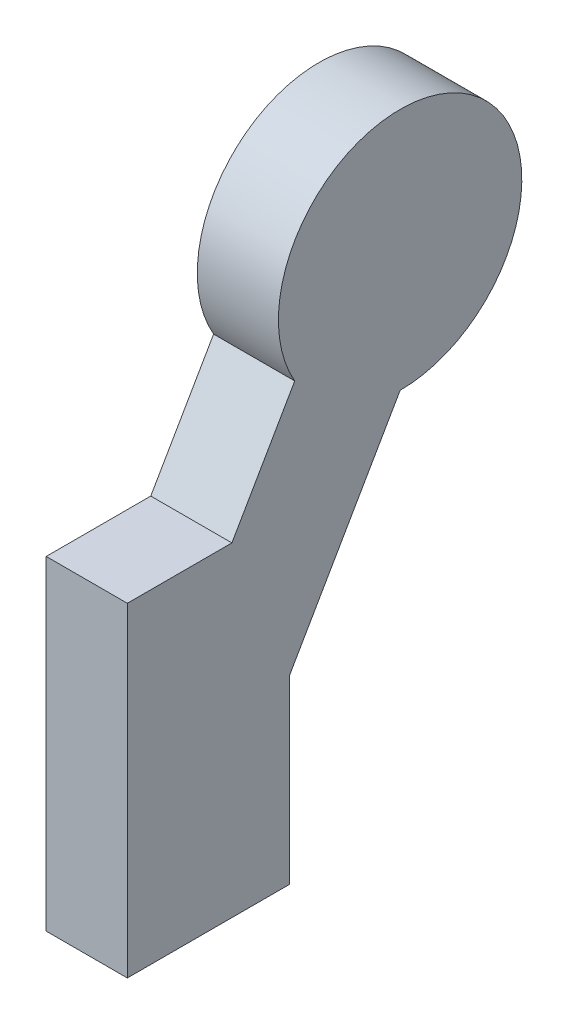
SolidWorks part; units mm, degrees
ref_plane "Front Plane" through (0, 0, 0) normal (0, 0, 1) x (1, 0, 0)
ref_plane "Top Plane" through (0, 0, 0) normal (0, 1, 0) x (1, 0, 0)
ref_plane "Right Plane" through (0, 0, 0) normal (1, 0, 0) x (0, 0, -1)
sketch "Sketch1" plane through (0, 0, 0) normal (1, 0, 0) x (0, 0, -1)
  line L0 (-6.35, 12.7) -> (6.35, -12.7) construction
  line L1 (-6.35, 12.7) -> (1.8331, 12.7)
  line L2 (-6.35, 12.7) -> (-6.35, -12.7)
  line L3 (-6.35, -12.7) -> (6.35, -12.7)
  line L4 (6.35, 1.4735) -> (6.35, -12.7)
  line L5 (0, 0) -> (56.9677, 98.671) construction
  line L6 (0, 0) -> (0, 52.5781) construction
  line L7 (6.7511, 21.2183) -> (1.8331, 12.7)
  line L8 (6.35, 1.4735) -> (15, 16.4558)
  line L9 (24.3594, 51.7168) -> (32.6083, 46.9543) construction
  arc A0 (15, 16.4558) -> (6.7511, 21.2183) centre (15, 25.9808) ccw
  point P16 (28.4839, 49.3355)
  dimension "D5" = 9.525
  dimension "D1" = 12.7
  dimension "D2" = 25.4
  dimension "D3" = 30
  dimension "D4" = 30
  dimension "D6" = 9.525
extrude "Boss-Extrude1" add sketch "Sketch1" along normal blind 6.35
